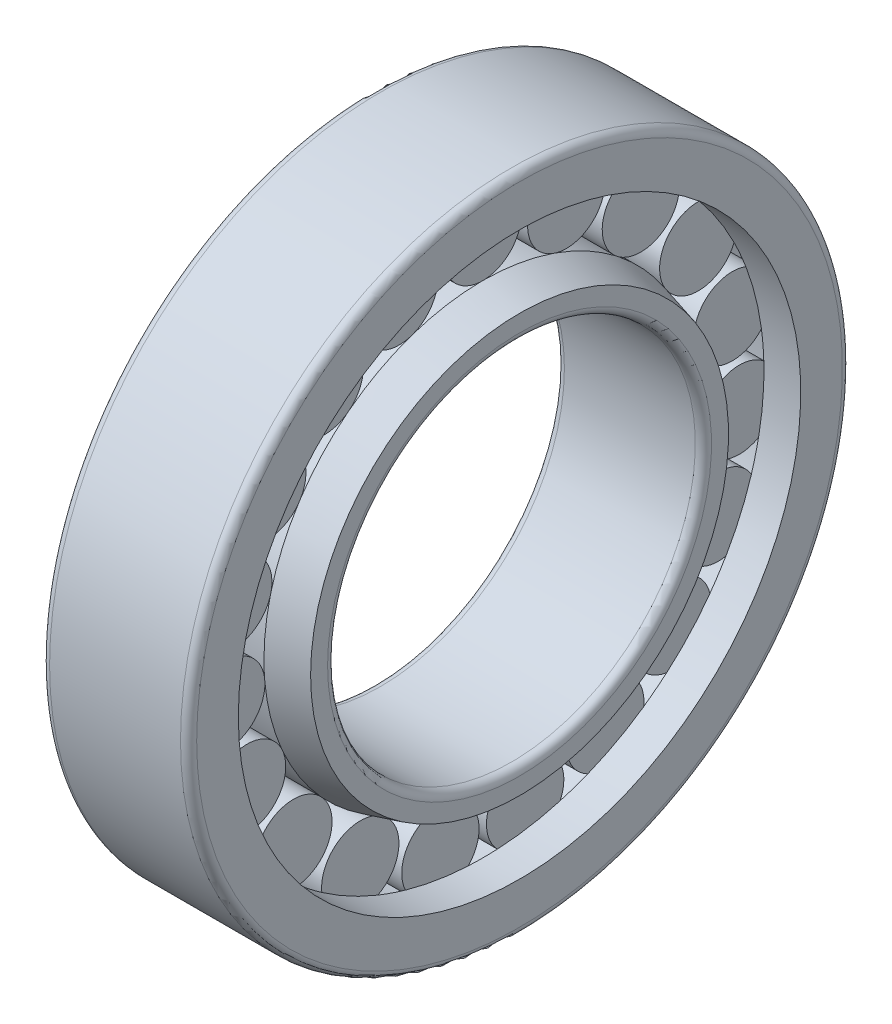
SolidWorks part; units mm, degrees
ref_plane "Front" through (0, 0, 0) normal (0, 0, 1) x (1, 0, 0)
ref_plane "Top" through (0, 0, 0) normal (0, 1, 0) x (1, 0, 0)
ref_plane "Right" through (0, 0, 0) normal (1, 0, 0) x (0, 0, -1)
other "Configuration Table"
sketch "Sketch1" plane through (0, 0, 0) normal (0, 0, 1) x (1, 0, 0)
  line L0 (-10, 25) -> (10, 25)
  line L1 (10, 25) -> (10, 28.4103)
  line L2 (10, 28.4103) -> (5, 29.75)
  line L3 (5, 29.75) -> (-5, 29.75)
  line L4 (-5, 29.75) -> (-10, 28.4103)
  line L5 (-10, 28.4103) -> (-10, 25)
  line L6 (-10.1379, 0) -> (10.5422, 0) construction
  dimension "B" = 20
  dimension "d" = 50
  dimension "FW" = 59.5
  dimension "D5" = 15
  dimension "D6" = 15
  dimension "D7" = 10
  dimension "D2" = 10
  dimension "D8" = 5
revolve "Revolve1" add sketch "Sketch1" angle 360 about L6
sketch "Sketch2" plane through (0, 0, 0) normal (0, 0, 1) x (1, 0, 0)
  line L0 (-5, 29.74) -> (5, 29.74)
  line L1 (5, 29.74) -> (5, 35)
  line L2 (-5, 35) -> (5, 35)
  line L3 (-5, 35) -> (-5, 29.74)
  line L4 (-7.1198, 0) -> (7.769, 0) construction
  line L6 (-7.4228, 35) -> (7.769, 35) construction
  dimension "D1" = 59.48
  dimension "D2" = 35
  dimension "D4" = 10
  dimension "D5" = 5
revolve "Revolve2" add sketch "Sketch2" angle 360 about L6
sketch "Sketch3" plane through (0, 0, 0) normal (0, 0, 1) x (1, 0, 0)
  line L0 (-10, 45) -> (10, 45)
  line L1 (10, 45) -> (10, 38.2375)
  line L2 (10, 38.2375) -> (4.99, 38.2375)
  line L3 (4.99, 38.2375) -> (4.99, 40.25)
  line L4 (4.99, 40.25) -> (-4.99, 40.25)
  line L5 (-4.99, 40.25) -> (-4.99, 38.2375)
  line L6 (-4.99, 38.2375) -> (-10, 38.2375)
  line L7 (-10, 38.2375) -> (-10, 45)
  line L8 (-9.0822, 0) -> (10.5352, 0) construction
  dimension "B" = 20
  dimension "DD" = 90
  dimension "D2" = 80.5
  dimension "D3" = 76.475
  dimension "D6" = 9.98
  dimension "D7" = 4.99
  dimension "D5" = 10
revolve "Revolve3" add sketch "Sketch3" angle 360 about L8
pattern_circular "Circular-Pattern1" count 19 over 360 about axis through (0, 0, 0) along (1, 0, 0) of "Revolve2"
fillet "Fillet1" radius 1.1 2 edges at (-10, 0, 45) (10, 0, 45)
fillet "Fillet2" radius 1.1 2 edges at (10, 0, 25) (-10, 0, 25)
equation "\"D2@Sketch1\" = \"B@Sketch1\" / 2"
equation "\"D7@Sketch1\" = \"D2@Sketch1\""
equation "\"D8@Sketch1\" = \"D7@Sketch1\"/2"
equation "\"D2@Sketch2\" = ( \"DD@Sketch3\" + \"d@Sketch1\" )  / 4"
equation "\"D4@Sketch2\" = \"B@Sketch1\" / 2"
equation "\"D5@Sketch2\" = \"D4@Sketch2\" / 2"
equation "\"D1@Sketch2\" = \"FW@Sketch1\" - 0.02"
equation "\"B@Sketch3\" = \"B@Sketch1\""
equation "\"D5@Sketch3\" = \"B@Sketch3\" / 2"
equation "\"D6@Sketch3\" = \"D5@Sketch3\" - 0.02"
equation "\"D7@Sketch3\" = \"D6@Sketch3\" / 2"
equation "\"D2@Sketch3\" = ( \"DD@Sketch3\" + \"d@Sketch1\" )  / 4 * 2 + ( ( \"DD@Sketch3\" + \"d@Sketch1\" )  / 4 * 2 - \"FW@Sketch1\"  ) "
equation "\"D3@Sketch3\" = \"D2@Sketch3\" * 0.95"
equation "\"m@Circular-Pattern1\"=int(3.14159265/atn(((\"DD@Sketch3\"+\"d@Sketch1\")/4-\"FW@Sketch1\"/2+0.02) / sqr((\"DD@Sketch3\"+\"d@Sketch1\")/4  * (\"DD@Sketch3\"+\"d@Sketch1\")/4 - ((\"DD@Sketch3\"+\"d@Sketch1\")/4-\"FW@Sketch1\"/2+0.02) *  ((\"DD@Sketch3\"+\"d@Sketch1\")/4-\"FW@Sketch1\"/2+0.02))))-1"
